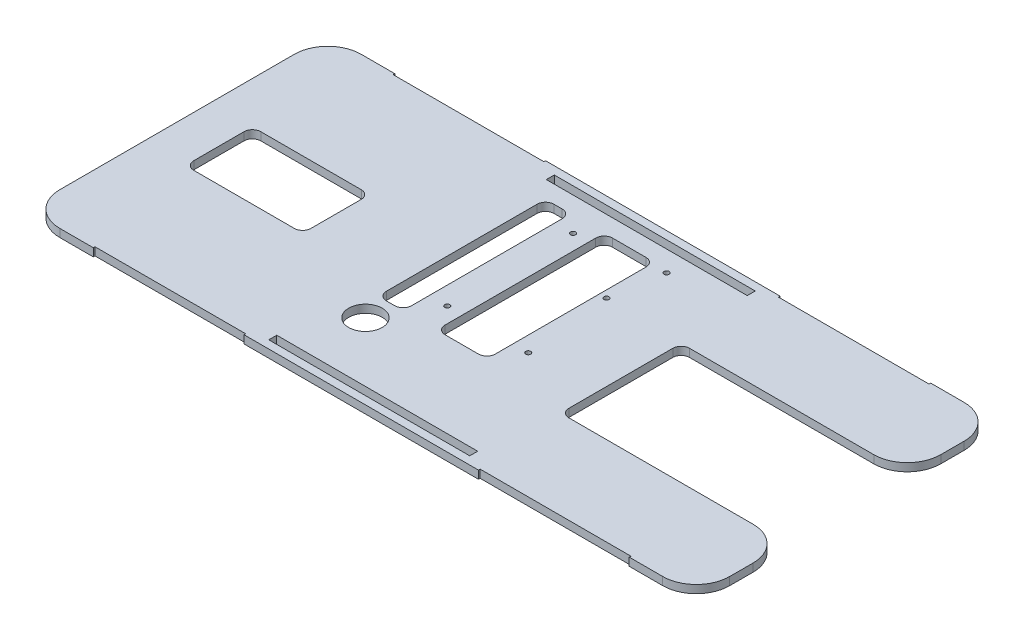
SolidWorks part; units mm, degrees
material "Teak"
ref_plane "Front Plane" through (0, 0, 0) normal (0, 0, 1) x (1, 0, 0)
ref_plane "Top Plane" through (0, 0, 0) normal (0, 1, 0) x (1, 0, 0)
ref_plane "Right Plane" through (0, 0, 0) normal (1, 0, 0) x (0, 0, -1)
sketch "Sketch1" plane through (0, 0, 0) normal (0, 1, 0) x (1, 0, 0)
  line L0 (-160, 89) -> (-160, -89) construction
  line L1 (-200, 90) -> (-160, 90)
  line L2 (-200, 90) -> (-200, -90)
  line L3 (-200, -90) -> (-160, -90)
  line L4 (200, 90) -> (200, -90)
  line L6 (-160, 90) -> (-160, 89)
  line L7 (-160, 89) -> (-70, 89)
  line L8 (-70, 90) -> (-70, 89)
  line L10 (-160, -90) -> (-160, -89)
  line L11 (-160, -89) -> (-70, -89)
  line L12 (-70, -90) -> (-70, -89)
  line L14 (70, -90) -> (70, -89)
  line L15 (70, -89) -> (160, -89)
  line L16 (160, -90) -> (160, -89)
  line L18 (70, 90) -> (70, 89)
  line L19 (70, 89) -> (160, 89)
  line L20 (160, 90) -> (160, 89)
  line L21 (-70, 89) -> (-70, -89) construction
  line L22 (70, -89) -> (-70, -89) construction
  line L23 (-70, 89) -> (70, 89) construction
  line L24 (70, -89) -> (70, 89) construction
  line L25 (-70, 90) -> (70, 90)
  line L26 (-70, -90) -> (70, -90)
  line L27 (160, -90) -> (200, -90)
  line L28 (160, 90) -> (200, 90)
  point P22 (200, 0)
  point P23 (-70, 0)
  point P24 (0, -89)
  dimension "D1" = 90
  dimension "D2" = 1
  dimension "D3" = 400
  dimension "D4" = 40
  dimension "D5" = 180
extrude "Boss-Extrude1" add sketch "Sketch1" along normal mid plane 4.7625
sketch "Sketch2" plane through (0, 2.3813, 0) normal (0, 1, 0) x (1, 0, 0)
  line L0 (200, -90) -> (200, 90) construction
  line L1 (200, 36) -> (65, 36)
  line L2 (200, 36) -> (200, -36)
  line L3 (200, -36) -> (65, -36)
  line L4 (65, 36) -> (65, -36)
  point P6 (65, 0)
  dimension "D1" = 72
  dimension "D2" = 135
extrude "Cut-Extrude1" cut sketch "Sketch2" against normal blind 10
sketch "Sketch3" plane through (0, 2.3813, 0) normal (0, 1, 0) x (1, 0, 0)
  line L0 (70, 90) -> (-70, 90) construction
  line L1 (-35, 70) -> (-50, 70)
  line L2 (-35, 70) -> (-35, -30)
  line L3 (-35, -30) -> (-50, -30)
  line L4 (-50, 70) -> (-50, -30)
  line L6 (-200, 90) -> (-200, -90) construction
  line L7 (-175, 20) -> (-105, 20)
  line L8 (-175, 20) -> (-175, -20)
  line L9 (-175, -20) -> (-105, -20)
  line L10 (-105, 20) -> (-105, -20)
  line L12 (-15, 70) -> (15, 70)
  line L13 (-15, 70) -> (-15, -30)
  line L14 (-15, -30) -> (15, -30)
  line L15 (15, 70) -> (15, -30)
  circle A0 centre (-42.5, -45) radius 10
  point P12 (-175, 0)
  point P20 (0, -30)
  point P25 (-42.5, -30)
  dimension "D11" = 20
  dimension "D1" = 100
  dimension "D2" = 15
  dimension "D3" = 20
  dimension "D4" = 20
  dimension "D5" = 70
  dimension "D6" = 40
  dimension "D7" = 25
  dimension "D8" = 30
  dimension "D9" = 100
  dimension "D10" = 20
  dimension "D12" = 15
extrude "Cut-Extrude2" cut sketch "Sketch3" against normal blind 10
sketch "Sketch4" plane through (0, 2.3813, 0) normal (0, 1, 0) x (1, 0, 0)
  circle A0 centre (24.1681, -14.4776) radius 1.5
  circle A1 centre (-24.1681, -14.4776) radius 1.5
  circle A2 centre (-24.1681, 60.6556) radius 1.5
  circle A3 centre (24.1681, 68.1486) radius 1.5
  circle A4 centre (19.2896, 37.1479) radius 1.5
  dimension "D1" = 3
  dimension "D2" = 3
extrude "Cut-Extrude3" cut sketch "Sketch4" against normal blind 10
sketch "Sketch5" plane through (0, 2.3813, 0) normal (0, 1, 0) x (1, 0, 0)
  line L0 (70, 90) -> (-70, 90) construction
  line L1 (-60, 85.2375) -> (60, 85.2375)
  line L2 (-60, 85.2375) -> (-60, 80.475)
  line L3 (-60, 80.475) -> (60, 80.475)
  line L4 (60, 85.2375) -> (60, 80.475)
  line L5 (-70, -90) -> (70, -90) construction
  line L6 (-60, -80.475) -> (60, -80.475)
  line L7 (-60, -80.475) -> (-60, -85.2375)
  line L8 (-60, -85.2375) -> (60, -85.2375)
  line L9 (60, -80.475) -> (60, -85.2375)
  point P4 (0, 80.475)
  dimension "D1" = 4.7625
  dimension "D2" = 120
  dimension "D3" = 4.7625
  dimension "D4" = 4.7625
extrude "Cut-Extrude4" cut sketch "Sketch5" against normal blind 10
fillet "Fillet1" radius 20 4 edges at (-200, 0, -90) (-200, 0, 90) (200, 0, -90) (200, 0, 90)
fillet "Fillet2" radius 20 2 edges at (200, 0, 36) (200, 0, -36)
fillet "Fillet3" radius 5 14 edges at (65, 0, -36) (65, 0, 36) (15, 0, -70) (15, 0, 30) (-15, 0, 30) (-15, 0, -70) (-35, 0, -70) (-50, 0, -70) (-35, 0, 30) (-50, 0, 30) (-105, 0, 20) (-175, 0, 20) (-175, 0, -20) (-105, 0, -20)
